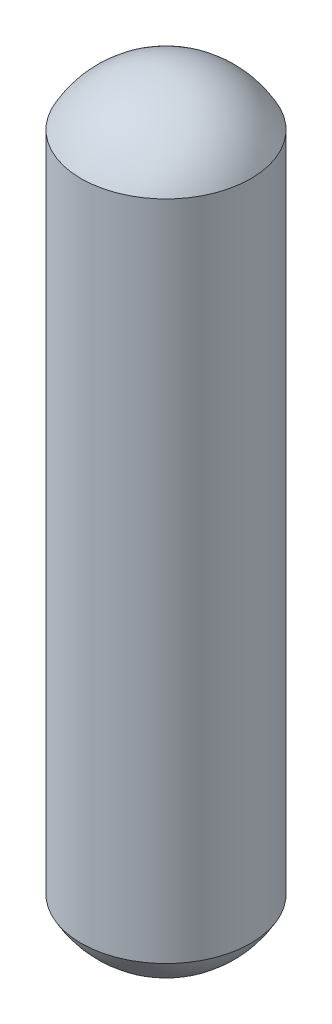
SolidWorks part; units mm, degrees
material "Plain Carbon Steel"
ref_plane "Front Plane" through (0, 0, 0) normal (0, 0, 1) x (1, 0, 0)
ref_plane "Top Plane" through (0, 0, 0) normal (0, 1, 0) x (1, 0, 0)
ref_plane "Right Plane" through (0, 0, 0) normal (1, 0, 0) x (0, 0, -1)
other "Configuration Table"
sketch "Sketch1" plane through (0, 0, 0) normal (0, 0, 1) x (1, 0, 0)
  line L0 (0, 5) -> (0, -23) construction
  line L1 (2, -1.2) -> (-2, -1.2) construction
  line L2 (2, -1.2) -> (2, -16.8)
  line L3 (2, -16.8) -> (-2, -16.8) construction
  line L4 (2, -18) -> (-2, -18) construction
  line L5 (0, -18) -> (0, 0)
  arc A0 (0, 0) -> (2, -1.2) centre (0, -2.2667) cw
  arc A1 (-2, -1.2) -> (0, 0) centre (0, -2.2667) cw construction
  arc A2 (2, -16.8) -> (0, -18) centre (0, -15.7333) cw
  arc A3 (0, -18) -> (-2, -16.8) centre (0, -15.7333) cw construction
  dimension "D1" = 1.2
  dimension "D2" = 4
  dimension "D3" = 1.2
  dimension "D4" = 5
  dimension "D5" = 5
  dimension "Length" = 18
revolve "Revolve1" add sketch "Sketch1" angle 360 about L0
